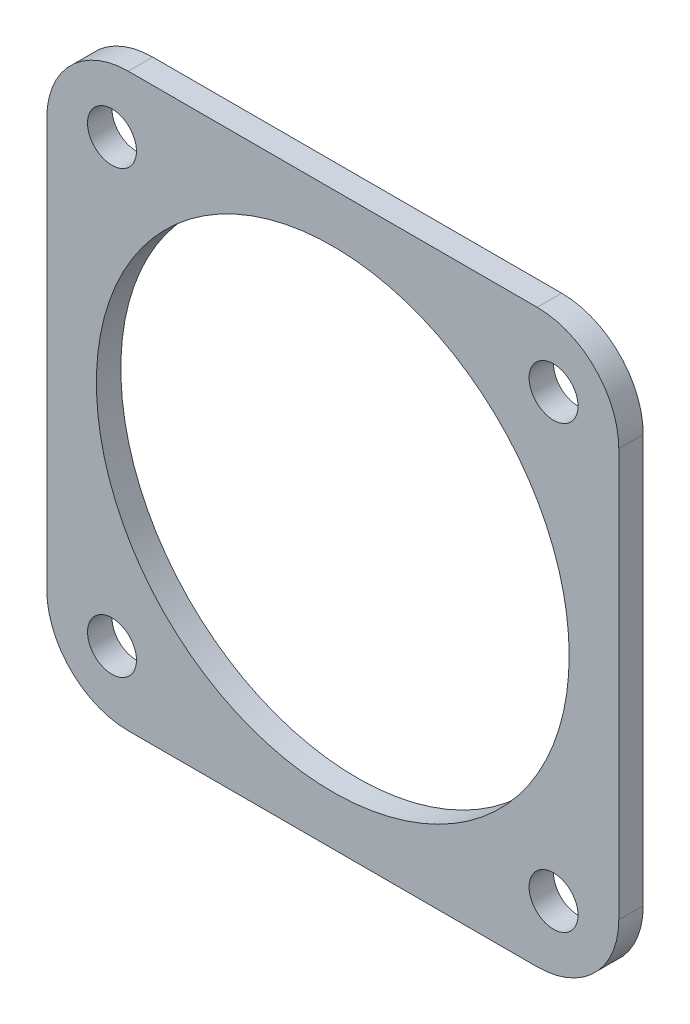
SolidWorks part; units mm, degrees
ref_plane "Alzado" through (0, 0, 0) normal (0, 0, 1) x (1, 0, 0)
ref_plane "Planta" through (0, 0, 0) normal (0, 1, 0) x (1, 0, 0)
ref_plane "Vista lateral" through (0, 0, 0) normal (1, 0, 0) x (0, 0, -1)
sketch "Croquis1" plane through (0, 0, 0) normal (0, 0, 1) x (1, 0, 0)
  line L1 (-35.0823, 35.0342) -> (35.0823, 35.0342)
  line L2 (-35.0823, 35.0342) -> (-35.0823, -35.0342)
  line L3 (-35.0823, -35.0342) -> (35.0823, -35.0342)
  line L4 (35.0823, 35.0342) -> (35.0823, -35.0342)
  line L5 (-35.0823, 35.0342) -> (35.0823, -35.0342) construction
  line L6 (-35.0823, -35.0342) -> (35.0823, 35.0342) construction
  circle A0 centre (0, 0) radius 29
  circle A1 centre (0, 0) radius 35
  dimension "D1" = 58
  dimension "D2" = 70
extrude "Saliente-Extruir1" add sketch "Croquis1" along normal blind 3 contours A1 A0 | L4 L1 L2 L3 A1
fillet "Redondeo1" radius 10 4 edges at (35.0823, -35.0342, 1.5) (-35.0823, -35.0342, 1.5) (-35.0823, 35.0342, 1.5) (35.0823, 35.0342, 1.5)
sketch "Croquis2" plane through (0, 0, 0) normal (0, 0, -1) x (-1, 0, 0)
  line L0 (-35.0823, 25.0342) -> (-35.0823, -25.0342) construction
  line L1 (25.0823, -35.0342) -> (-25.0823, -35.0342) construction
  line L2 (25.0823, 35.0342) -> (-25.0823, 35.0342) construction
  line L3 (35.0823, 25.0342) -> (35.0823, -25.0342) construction
  circle A0 centre (-27.0823, 27.0342) radius 3
  circle A1 centre (27.0823, 27.0342) radius 3
  circle A2 centre (-27.0823, -27.0342) radius 3
  circle A3 centre (27.0823, -27.0342) radius 3
  dimension "D9" = 6
  dimension "D10" = 6
  dimension "D11" = 6
  dimension "D12" = 6
  dimension "D1" = 8
  dimension "D2" = 8
  dimension "D3" = 8
  dimension "D4" = 8
  dimension "D5" = 8
  dimension "D6" = 8
  dimension "D7" = 8
  dimension "D8" = 8
extrude "Cortar-Extruir1" cut sketch "Croquis2" against normal blind 10 contours A1 | A0 | A2 | A3
